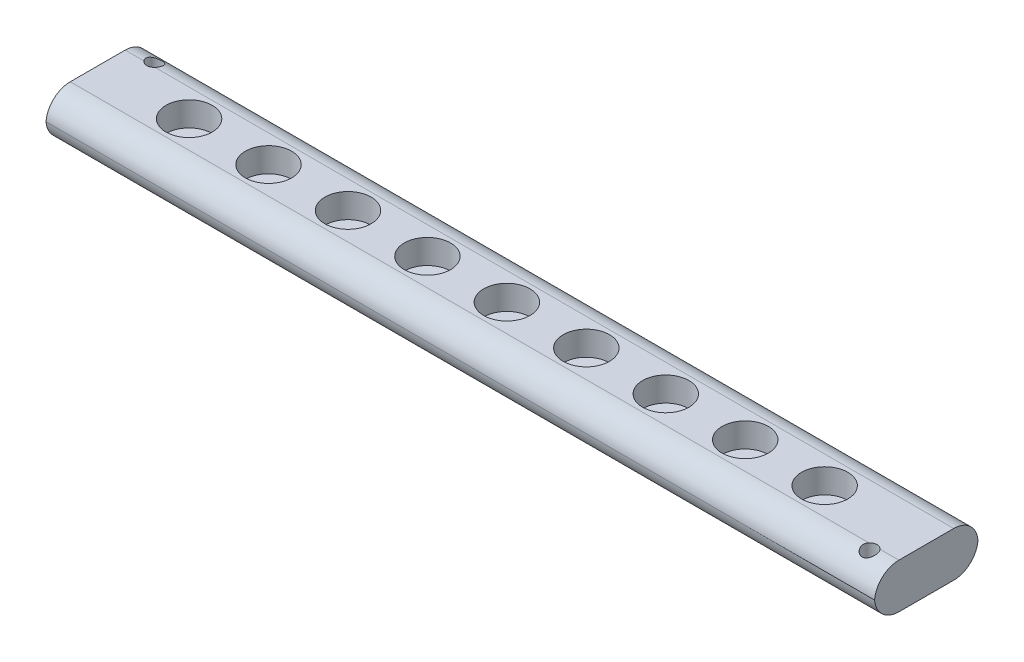
SolidWorks part; units mm, degrees
ref_plane "Front Plane" through (0, 0, 0) normal (0, 0, 1) x (1, 0, 0)
ref_plane "Top Plane" through (0, 0, 0) normal (0, 1, 0) x (1, 0, 0)
ref_plane "Right Plane" through (0, 0, 0) normal (1, 0, 0) x (0, 0, -1)
sketch "Sketch1" plane through (0, 0, 0) normal (0, 1, 0) x (1, 0, 0)
  line L1 (-43.1855, 16.9657) -> (296.8145, 16.9657)
  line L2 (-43.1855, 16.9657) -> (-43.1855, -25.5343)
  line L3 (-43.1855, -25.5343) -> (296.8145, -25.5343)
  line L4 (296.8145, 16.9657) -> (296.8145, -25.5343)
  dimension "D1" = 42.5
  dimension "D2" = 340
extrude "Boss-Extrude1" add sketch "Sketch1" along normal blind 41.5
sketch "Sketch2" plane through (0, 41.5, 0) normal (0, 1, 0) x (1, 0, 0)
  circle A0 centre (-5.6855, -4.2843) radius 9.5
  circle A1 centre (26.9145, -4.2843) radius 9.5
  circle A2 centre (59.5145, -4.2843) radius 9.5
  circle A3 centre (92.1145, -4.2843) radius 9.5
  circle A4 centre (124.7145, -4.2843) radius 9.5
  circle A5 centre (157.3145, -4.2843) radius 9.5
  circle A6 centre (189.9145, -4.2843) radius 9.5
  circle A7 centre (222.5145, -4.2843) radius 9.5
  circle A8 centre (255.1145, -4.2843) radius 9.5
extrude "Cut-Extrude1" cut sketch "Sketch2" against normal blind 10
sketch "Sketch3" plane through (-43.1855, 0, 0) normal (-1, 0, 0) x (0, 0, 1)
  line L0 (-16.9657, 41.5) -> (25.5343, 41.5)
  line L1 (-6.9657, 41.5) -> (15.5343, 41.5)
  line L2 (-16.9657, 31.5) -> (-16.9657, 10)
  line L3 (-6.9657, 0) -> (15.5343, 0)
  line L4 (25.5343, 31.5) -> (25.5343, 10)
  line L5 (25.5343, 41.5) -> (25.5343, 0)
  line L6 (25.5343, 0) -> (-16.9657, 0)
  line L7 (-16.9657, 0) -> (-16.9657, 41.5)
  arc A0 (-16.9657, 10) -> (-6.9657, 0) centre (-6.9657, 10) ccw
  arc A1 (15.5343, 0) -> (25.5343, 10) centre (15.5343, 10) ccw
  arc A2 (15.5343, 41.5) -> (25.5343, 31.5) centre (15.5343, 31.5) cw
  arc A3 (-6.9657, 41.5) -> (-16.9657, 31.5) centre (-6.9657, 31.5) ccw
  point P10 (25.5343, 0)
  point P15 (-16.9657, 41.5)
  line M1 (-16.9657, 0) -> (25.5343, 0)
  line M2 (25.5343, 0) -> (25.5343, 41.5)
  line M3 (25.5343, 41.5) -> (-16.9657, 41.5)
  line M4 (-16.9657, 41.5) -> (-16.9657, 0)
  dimension "D1" = 10
sketch "Sketch4" plane through (0, 41.5, 0) normal (0, 1, 0) x (1, 0, 0)
  circle A0 centre (286.8145, -17.5343) radius 3.05
  circle A2 centre (-33.1855, 8.9657) radius 3.05
extrude "Cut-Extrude3" cut sketch "Sketch4" against normal through all
extrude "Cut-Extrude4" cut sketch "Sketch3" against normal through all contours A3 M3 M4 | A0 M4 M1 | A1 M1 M2 | A2 M3 M2
sketch "Sketch5" plane through (-43.1855, 0, 0) normal (-1, 0, 0) x (0, 0, 1)
  line L0 (4.2843, 41.5) -> (4.2843, 23.1)
  line L1 (-6.9657, 41.5) -> (15.5343, 41.5) construction
  line L2 (4.2843, 23.1) -> (25.5343, 23.1)
  line L3 (25.5343, 31.5) -> (25.5343, 10) construction
  line L4 (4.2843, 23.1) -> (-16.9657, 23.1)
  line L5 (-16.9657, 31.5) -> (-16.9657, 10) construction
  line L7 (-16.9657, 23.1) -> (25.5343, 23.1)
  line L8 (-16.9657, 23.1) -> (-16.9657, 0)
  line L9 (-16.9657, 0) -> (25.5343, 0)
  line L10 (25.5343, 23.1) -> (25.5343, 0)
  line M1 (25.5343, 10) -> (25.5343, 31.5)
  line M5 (-16.9657, 31.5) -> (-16.9657, 10)
  arc M6 (-16.9657, 10) -> (-6.9657, 0) centre (-6.9657, 10) ccw
  line M7 (-6.9657, 0) -> (15.5343, 0)
  arc M8 (15.5343, 0) -> (25.5343, 10) centre (15.5343, 10) ccw
extrude "Cut-Extrude5" cut sketch "Sketch5" against normal through all contours L2 L4 M5 M6 M7 M8 M1
sketch "Sketch6" plane through (-43.1855, 0, 0) normal (-1, 0, 0) x (0, 0, 1)
  line L0 (-16.9657, 33.1) -> (-16.9657, 23.1)
  line L1 (-6.9657, 23.1) -> (15.5343, 23.1)
  line L2 (-16.9657, 33.1) -> (-16.9657, 41.5)
  line L3 (-16.9657, 41.5) -> (15.5343, 41.5)
  line L4 (-16.9657, 23.1) -> (25.5343, 23.1)
  line L5 (15.5343, 23.1) -> (-6.9657, 23.1)
  line L6 (25.5343, 33.1) -> (25.5343, 41.5)
  line L7 (25.5343, 41.5) -> (-6.9657, 41.5)
  line L8 (25.5343, 23.1) -> (25.5343, 33.1)
  arc A0 (15.5343, 23.1) -> (25.5343, 33.1) centre (15.5343, 33.1) ccw
  arc A1 (-16.9657, 33.1) -> (-6.9657, 23.1) centre (-6.9657, 33.1) ccw
  point P14 (25.5343, 23.1)
  point P17 (-16.9657, 23.1)
  line M1 (-16.9657, 23.1) -> (25.5343, 23.1)
  line M2 (25.5343, 23.1) -> (25.5343, 31.5)
  arc M3 (25.5343, 31.5) -> (15.5343, 41.5) centre (15.5343, 31.5) ccw
  arc M5 (-6.9657, 41.5) -> (-16.9657, 31.5) centre (-6.9657, 31.5) ccw
  line M6 (-16.9657, 31.5) -> (-16.9657, 23.1)
  dimension "D1" = 10
extrude "Cut-Extrude6" cut sketch "Sketch6" against normal through all contours A1 M5 M6 M1 | A0 M1 M2 M3
